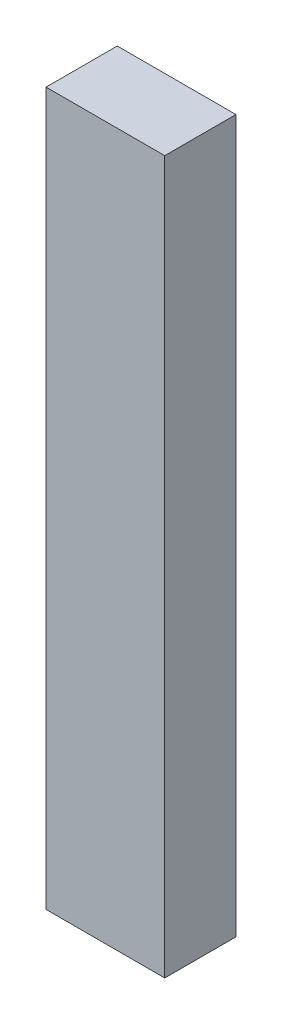
SolidWorks part; units mm, degrees
ref_plane "Front Plane" through (0, 0, 0) normal (0, 0, 1) x (1, 0, 0)
ref_plane "Top Plane" through (0, 0, 0) normal (0, 1, 0) x (1, 0, 0)
ref_plane "Right Plane" through (0, 0, 0) normal (1, 0, 0) x (0, 0, -1)
sketch "Sketch1" plane through (0, 0, 0) normal (0, 0, 1) x (1, 0, 0)
  line L1 (5, 15) -> (10, 15)
  line L2 (5, 15) -> (5, -15)
  line L3 (5, -15) -> (10, -15)
  line L4 (10, 15) -> (10, -15)
  dimension "D1" = 15
  dimension "D2" = 30
  dimension "D3" = 10
  dimension "D4" = 5
extrude "Boss-Extrude1" add sketch "Sketch1" along normal blind 3
